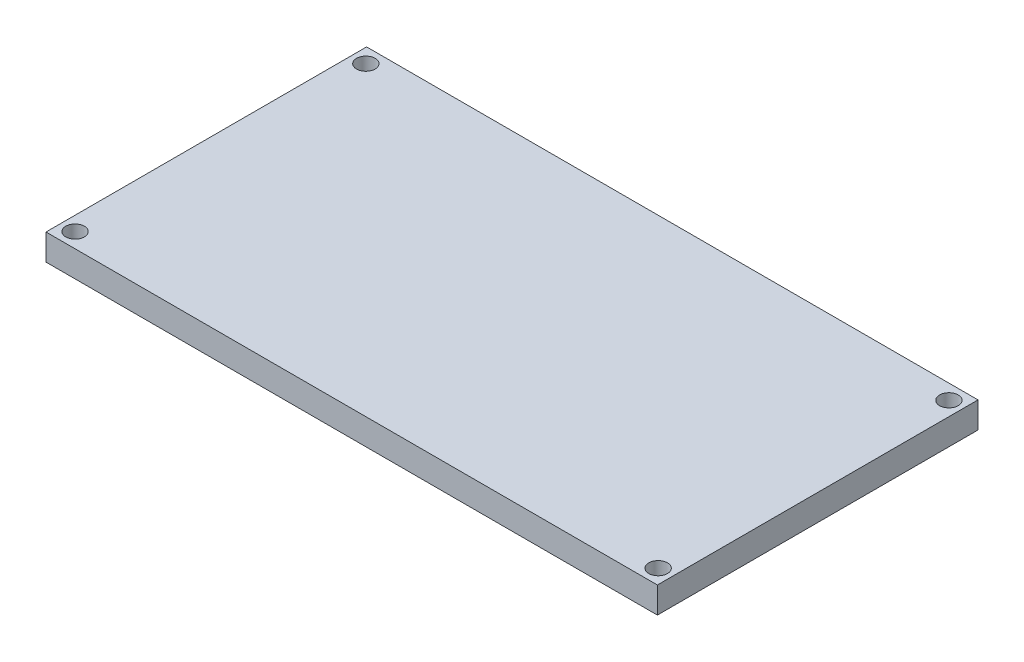
SolidWorks part; units mm, degrees
ref_plane "Front Plane" through (0, 0, 0) normal (0, 0, 1) x (1, 0, 0)
ref_plane "Top Plane" through (0, 0, 0) normal (0, 1, 0) x (1, 0, 0)
ref_plane "Right Plane" through (0, 0, 0) normal (1, 0, 0) x (0, 0, -1)
sketch "Sketch2" plane through (0, 0, 0) normal (0, 1, 0) x (1, 0, 0)
  line L1 (-52.07, -27.305) -> (52.07, -27.305)
  line L2 (-52.07, -27.305) -> (-52.07, 27.305)
  line L3 (-52.07, 27.305) -> (52.07, 27.305)
  line L4 (52.07, -27.305) -> (52.07, 27.305)
  line L5 (-52.07, -27.305) -> (52.07, 27.305) construction
  line L6 (-52.07, 27.305) -> (52.07, -27.305) construction
  point P0 (0, 0)
  dimension "D1" = 54.61
  dimension "D2" = 104.14
extrude "Boss-Extrude1" add sketch "Sketch2" along normal blind 4.445
sketch "Sketch3" plane through (0, 4.445, 0) normal (0, 1, 0) x (1, 0, 0)
  line L1 (-49.657, -24.765) -> (49.657, -24.765) construction
  line L2 (-49.657, -24.765) -> (-49.657, 24.765) construction
  line L3 (-49.657, 24.765) -> (49.657, 24.765) construction
  line L4 (49.657, -24.765) -> (49.657, 24.765) construction
  line L5 (-49.657, -24.765) -> (49.657, 24.765) construction
  line L6 (-49.657, 24.765) -> (49.657, -24.765) construction
  circle A0 centre (-49.657, 24.765) radius 1.5875
  circle A1 centre (49.657, 24.765) radius 1.5875
  circle A2 centre (49.657, -24.765) radius 1.5875
  circle A3 centre (-49.657, -24.765) radius 1.5875
  point P0 (0, 0)
  dimension "D3" = 3.175
  dimension "D1" = 49.53
  dimension "D2" = 99.314
extrude "Cut-Extrude1" cut sketch "Sketch3" against normal through all both and the other way through all
